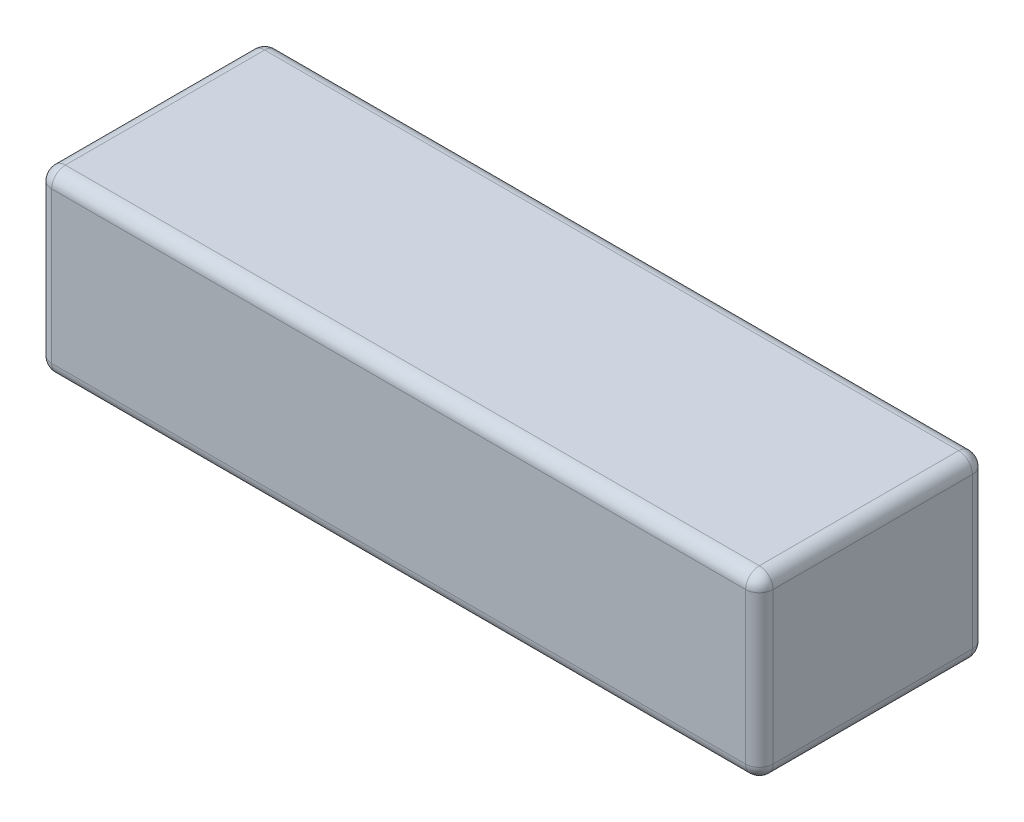
SolidWorks part; units mm, degrees
ref_plane "前基準面" through (0, 0, 0) normal (0, 0, 1) x (1, 0, 0)
ref_plane "上基準面" through (0, 0, 0) normal (0, 1, 0) x (1, 0, 0)
ref_plane "右基準面" through (0, 0, 0) normal (1, 0, 0) x (0, 0, -1)
sketch "草圖1" plane through (0, 0, 0) normal (0, 1, 0) x (1, 0, 0)
  line L1 (-52.5, 16.5) -> (52.5, 16.5)
  line L2 (-52.5, 16.5) -> (-52.5, -16.5)
  line L3 (-52.5, -16.5) -> (52.5, -16.5)
  line L4 (52.5, 16.5) -> (52.5, -16.5)
  line L5 (-52.5, 16.5) -> (52.5, -16.5) construction
  line L6 (-52.5, -16.5) -> (52.5, 16.5) construction
  point P0 (0, 0)
  dimension "D1" = 105
  dimension "D2" = 33
extrude "填料-伸長1" add sketch "草圖1" along normal blind 26
fillet "圓角1" radius 2 12 edges at (0, 26, -16.5) (52.5, 26, 0) (52.5, 13, -16.5) (-52.5, 13, -16.5) (-52.5, 26, 0) (-52.5, 13, 16.5) (0, 26, 16.5) (52.5, 13, 16.5) (0, 0, -16.5) (-52.5, 0, 0) (0, 0, 16.5) (52.5, 0, 0)
